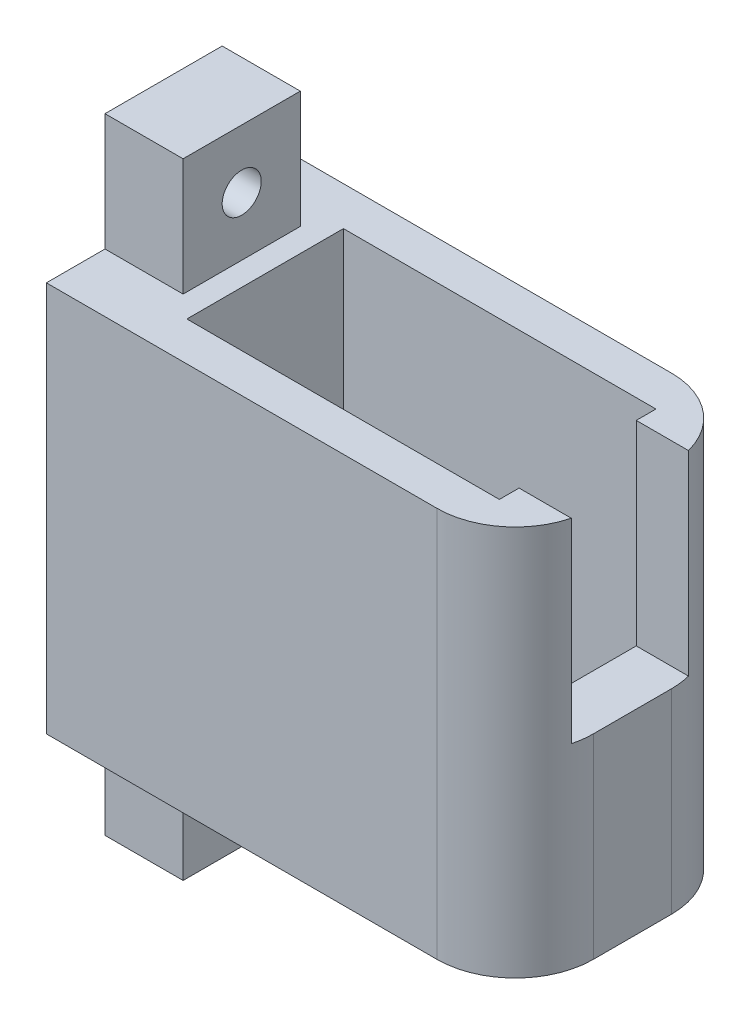
SolidWorks part; units mm, degrees
ref_plane "Front Plane" through (0, 0, 0) normal (0, 0, 1) x (1, 0, 0)
ref_plane "Top Plane" through (0, 0, 0) normal (0, 1, 0) x (1, 0, 0)
ref_plane "Right Plane" through (0, 0, 0) normal (1, 0, 0) x (0, 0, -1)
sketch "Sketch1" plane through (0, 0, 0) normal (0, 0, 1) x (1, 0, 0)
  line L0 (-10, 40) -> (-10, -40)
  line L1 (-10, -40) -> (0, -40)
  line L2 (0, -40) -> (0, -25)
  line L3 (0, -25) -> (50, -25)
  line L4 (50, -25) -> (50, 25)
  line L5 (50, 25) -> (0, 25)
  line L6 (0, 25) -> (0, 40)
  line L7 (0, 40) -> (-10, 40)
  point P10 (-10, 0)
  dimension "D1" = 80
  dimension "D2" = 50
  dimension "D3" = 50
  dimension "D4" = 10
extrude "Boss-Extrude1" add sketch "Sketch1" along normal mid plane 30
sketch "Sketch2" plane through (50, 0, 0) normal (1, 0, 0) x (0, 0, -1)
  line L0 (-15, 25) -> (15, 25) construction
  line L1 (-10.02, 25) -> (10.02, 25)
  line L2 (-10.02, 25) -> (-10.02, -20)
  line L3 (-10.02, -20) -> (10.02, -20)
  line L4 (10.02, 25) -> (10.02, -20)
  line L5 (-15, -25) -> (15, -25) construction
  point P6 (0, 25)
  dimension "D1" = 20.04
  dimension "D2" = 5
extrude "Cut-Extrude1" cut sketch "Sketch2" against normal blind 40 from offset 7 offset against normal yes
sketch "Sketch4" plane through (50, 0, 0) normal (1, 0, 0) x (0, 0, -1)
  line L0 (15, -25) -> (15, 25) construction
  line L1 (-15, -25) -> (15, -25)
  line L2 (-15, -25) -> (-15, -23)
  line L3 (-15, -23) -> (15, -23)
  line L4 (15, -25) -> (15, -23)
  line L5 (-15, 25) -> (15, 25) construction
  dimension "D1" = 48
sketch "Sketch5" plane through (0, -20, 0) normal (0, 1, 0) x (1, 0, 0)
  line L0 (3, 10.02) -> (43, 10.02) construction
  line L1 (43, -10.02) -> (43, 10.02) construction
  line L2 (3, -10.02) -> (43, -10.02) construction
  circle A0 centre (32.98, 0) radius 10.02
extrude "Cut-Extrude2" cut sketch "Sketch5" against normal blind 40
sketch "Sketch6" plane through (50, 0, 0) normal (1, 0, 0) x (0, 0, -1)
  line L0 (-15, 25) -> (15, 25) construction
  line L1 (-7.5, 0) -> (7.5, 0)
  line L2 (-7.5, 0) -> (-7.5, 25)
  line L3 (-7.5, 25) -> (7.5, 25)
  line L4 (7.5, 0) -> (7.5, 25)
  line L5 (-7.5, 0) -> (7.5, 25) construction
  line L6 (-7.5, 25) -> (7.5, 0) construction
  point P0 (0, 12.5)
  dimension "D1" = 15
extrude "Cut-Extrude3" cut sketch "Sketch6" against normal blind 40
sketch "Sketch7" plane through (0, 0, 0) normal (1, 0, 0) x (0, 0, -1)
  line L0 (-15, 25) -> (15, 25) construction
  line L1 (15, 40) -> (7.5, 40)
  line L2 (15, 40) -> (15, 25)
  line L3 (15, 25) -> (7.5, 25)
  line L4 (7.5, 40) -> (7.5, 25)
  line L5 (-15, -25) -> (15, -25) construction
  line L6 (-15, 40) -> (-7.5, 40)
  line L7 (-15, 40) -> (-15, 25)
  line L8 (-15, 25) -> (-7.5, 25)
  line L9 (-7.5, 40) -> (-7.5, 25)
  line L10 (-15, -40) -> (-7.5, -40)
  line L11 (-15, -40) -> (-15, -25)
  line L12 (-15, -25) -> (-7.5, -25)
  line L13 (-7.5, -40) -> (-7.5, -25)
  line L14 (-15, 40) -> (15, 40) construction
  line L15 (15, -40) -> (7.5, -40)
  line L16 (15, -40) -> (15, -25)
  line L17 (15, -25) -> (7.5, -25)
  line L18 (7.5, -40) -> (7.5, -25)
  line L19 (-15, -40) -> (15, -40) construction
  circle A0 centre (0, 32.5) radius 2.5
  circle A1 centre (0, -32.5) radius 2.5
  dimension "D1" = 5
  dimension "D2" = 5
  dimension "D3" = 15
  dimension "D4" = 7.5
  dimension "D5" = 7.5
extrude "Cut-Extrude4" cut sketch "Sketch7" against normal blind 40
fillet "Fillet1" radius 10 2 edges at (50, 0, -15) (50, 0, 15)
